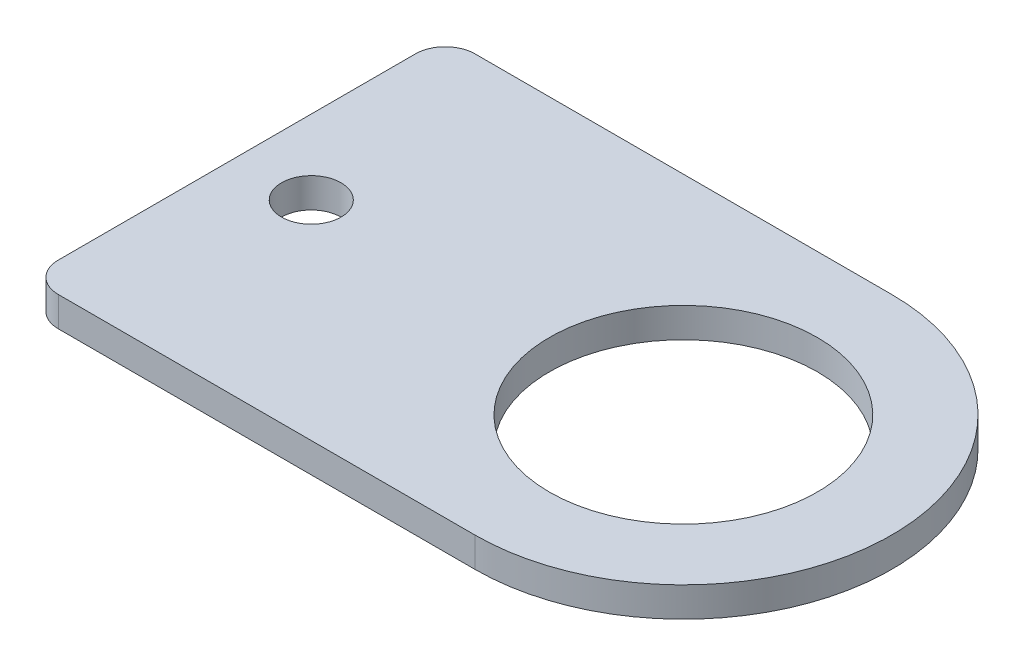
SolidWorks part; units mm, degrees
ref_plane "Front Plane" through (0, 0, 0) normal (0, 0, 1) x (1, 0, 0)
ref_plane "Top Plane" through (0, 0, 0) normal (0, 1, 0) x (1, 0, 0)
ref_plane "Right Plane" through (0, 0, 0) normal (1, 0, 0) x (0, 0, -1)
sketch "Sketch1" plane through (0, 0, 0) normal (0, 1, 0) x (1, 0, 0)
  line L0 (-15, 0) -> (-10, 0) construction
  line L1 (-15, -14) -> (15, -14)
  line L2 (-15, -14) -> (-15, 14)
  line L3 (-15, 14) -> (15, 14)
  line L5 (-15, -14) -> (15, 14) construction
  line L6 (-15, 14) -> (15, -14) construction
  arc A0 (15, 14) -> (15, -14) centre (15, 0) cw
  circle A1 centre (-10, 0) radius 2
  circle A2 centre (15, 0) radius 9
  point P0 (0, 0)
  dimension "D1" = 30
  dimension "D2" = 28
extrude "Boss-Extrude1" add sketch "Sketch1" along normal blind 2
fillet "Fillet1" radius 2 2 edges at (-15, 1, -14) (-15, 1, 14)
